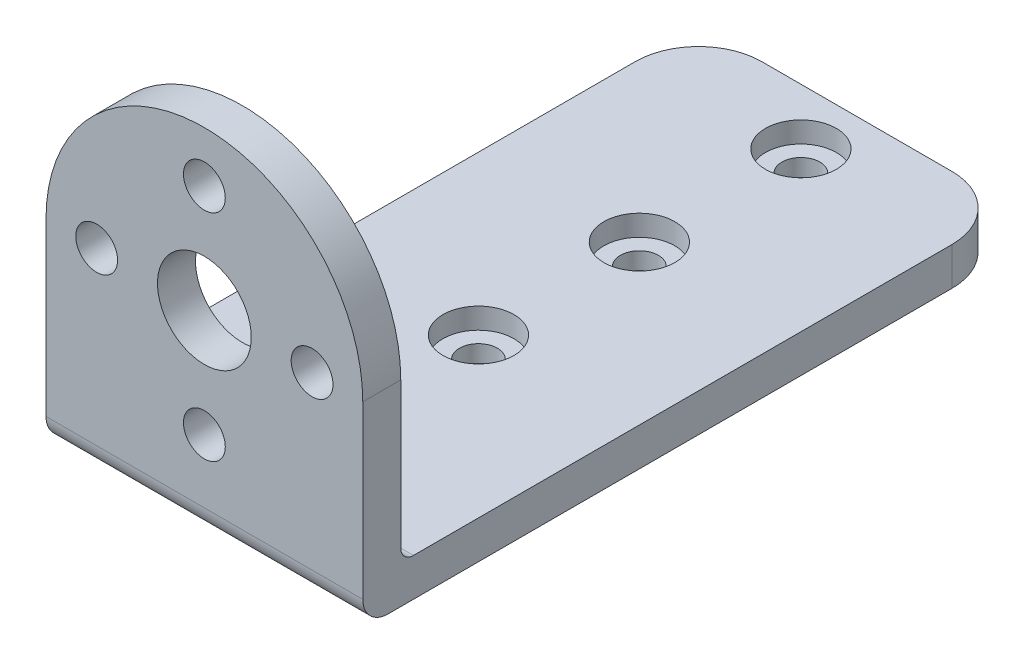
SolidWorks part; units mm, degrees
material "ABS"
ref_plane "Plano frontal" through (0, 0, 0) normal (0, 0, 1) x (1, 0, 0)
ref_plane "Plano superior" through (0, 0, 0) normal (0, 1, 0) x (1, 0, 0)
ref_plane "Plano direito" through (0, 0, 0) normal (1, 0, 0) x (0, 0, -1)
sketch "Esboço1" plane through (0, 0, 0) normal (0, 1, 0) x (1, 0, 0)
  line L1 (0, 0) -> (25, 0)
  line L2 (0, 0) -> (0, 51.5)
  line L3 (0, 51.5) -> (25, 51.5)
  line L4 (25, 0) -> (25, 51.5)
  dimension "D1" = 51.5
  dimension "D2" = 25
extrude "Ressalto-extrusão1" add sketch "Esboço1" along normal blind 3
sketch "Esboço4" plane through (0, 3, 0) normal (0, 1, 0) x (1, 0, 0)
  line L0 (25, 0) -> (25, 51.5) construction
  line L1 (0, 0) -> (25, 0)
  line L2 (0, 0) -> (0, 3)
  line L3 (0, 3) -> (25, 3)
  line L4 (25, 0) -> (25, 3)
  dimension "D1" = 3
extrude "Ressalto-extrusão2" add sketch "Esboço4" along normal blind 25
sketch "Esboço5" plane through (0, 0, 0) normal (0, 0, 1) x (1, 0, 0)
  line L0 (0, 28) -> (25, 3) construction
  line L1 (25, 28) -> (0, 3) construction
  line L2 (25, 28) -> (25, 0) construction
  line L3 (0, 28) -> (25, 28) construction
  line L4 (0, 15.5) -> (25, 15.5) construction
  line L5 (12.5, 28) -> (12.5, 0) construction
  line L6 (0, 0) -> (25, 0) construction
  arc A0 (25, 15.5) -> (0, 15.5) centre (12.5, 15.5) ccw
  circle A1 centre (12.5, 15.5) radius 3.7
  circle A2 centre (4, 15.5) radius 1.65
  circle A3 centre (12.5, 24) radius 1.65
  circle A4 centre (21, 15.5) radius 1.65
  circle A5 centre (12.5, 7) radius 1.65
  line M2 (25, 0) -> (25, 28)
  line M3 (25, 28) -> (0, 28)
  line M4 (0, 28) -> (0, 0)
  dimension "D1" = 7.4
  dimension "D2" = 3.3
  dimension "D3" = 8.5
  dimension "D4" = 4
extrude "Corte-extrusão1" cut sketch "Esboço5" against normal blind 25 contours A2 | A0 M3 M4 | A3 | A1 | A4 | A5 | A0 M2 M3
sketch "Esboço7" plane through (0, 3, 0) normal (0, 1, 0) x (1, 0, 0)
  line L1 (25, 3) -> (25, 51.5) construction
  line L2 (25, 51.5) -> (0, 51.5) construction
  line L26 (12.5, 51.5) -> (12.5, 3) construction
  line L27 (25, 3) -> (0, 3) construction
  line L47 (0, 40.68) -> (25, 40.68) construction
  circle A43 centre (12.5, 34.33) radius 1.5
  circle A45 centre (12.5, 21.63) radius 1.5
  circle A47 centre (12.5, 8.93) radius 1.5
  circle A48 centre (12.5, 47.08) radius 1.5
extrude "Corte-extrusão2" cut sketch "Esboço7" against normal blind 25
fillet "Filete1" radius 5 2 edges at (0, 1.5, -51.5) (25, 1.5, -51.5)
fillet "Filete2" radius 2 1 edges at (12.5, 0, 0)
fillet "Filete3" radius 1 1 edges
sketch "Esboço8" plane through (0, 3, 0) normal (0, 1, 0) x (1, 0, 0)
  circle A0 centre (12.5, 47.08) radius 2.8
  circle A1 centre (12.5, 34.33) radius 2.8
  circle A2 centre (12.5, 21.63) radius 2.8
  circle A3 centre (12.5, 8.93) radius 2.8
extrude "Corte-extrusão3" cut sketch "Esboço8" against normal blind 1.65
